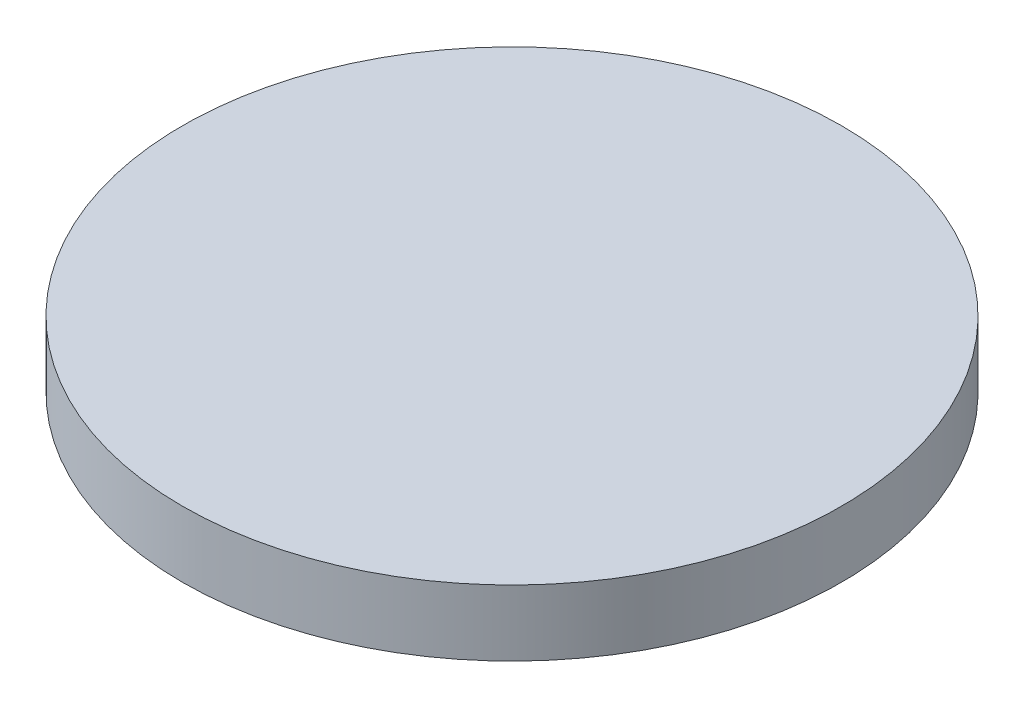
SolidWorks part; units mm, degrees
ref_plane "Front" through (0, 0, 0) normal (0, 0, 1) x (1, 0, 0)
ref_plane "Top" through (0, 0, 0) normal (0, 1, 0) x (1, 0, 0)
ref_plane "Right" through (0, 0, 0) normal (1, 0, 0) x (0, 0, -1)
sketch "草图1" plane through (0, 0, 0) normal (0, 1, 0) x (1, 0, 0)
  circle A0 centre (0, 0) radius 250
  dimension "D1" = 500
extrude "凸台-拉伸1" add sketch "草图1" along normal blind 50
sketch "草图2" plane through (0, 0, 0) normal (1, 0, 0) x (0, 0, -1)
  line L0 (-250, 50) -> (-250, 0) construction
  point P0 (-250, 25)
  point P1 (0, 25)
